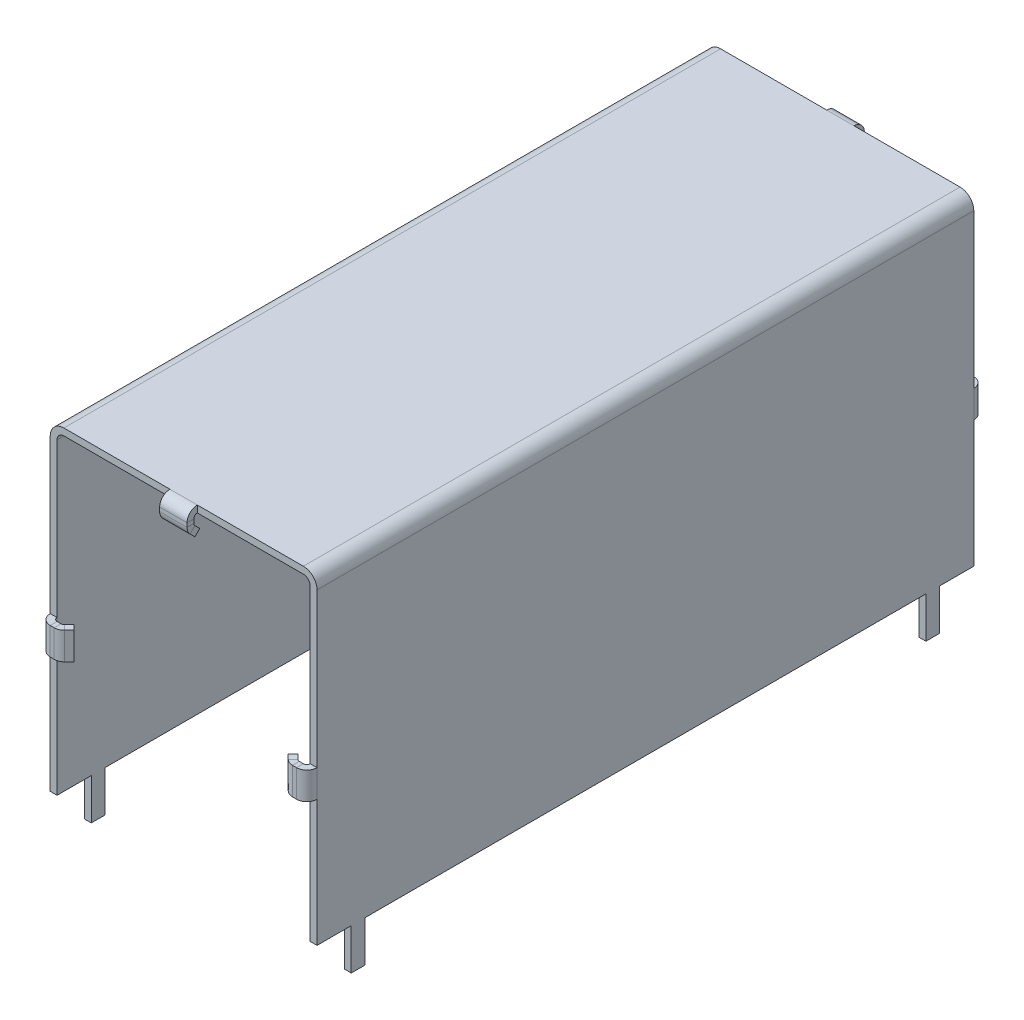
SolidWorks part; units mm, degrees
ref_plane "Спереди" through (0, 0, 0) normal (0, 0, 1) x (1, 0, 0)
ref_plane "Сверху" through (0, 0, 0) normal (0, 1, 0) x (1, 0, 0)
ref_plane "Справа" through (0, 0, 0) normal (1, 0, 0) x (0, 0, -1)
sketch "Эскиз1" plane through (0, 0, 0) normal (0, 0, 1) x (1, 0, 0)
  line L0 (0.5, 0) -> (0.5, 25.5)
  line L1 (0, 0) -> (0.5, 0)
  line L2 (0, 0) -> (0, 25.5)
  line L3 (1, 26.5) -> (18.5, 26.5)
  line L4 (19.5, 0) -> (19.5, 25.5)
  line L9 (1, 26) -> (18.5, 26)
  line L10 (19, 0) -> (19, 25.5)
  line L12 (0.5, 0.5) -> (19, 0.5) construction
  line L13 (0.5, 0.5) -> (0.5, 26) construction
  line L14 (19, 0.5) -> (19, 26) construction
  line L15 (19, 0) -> (19.5, 0)
  line L16 (0, 0) -> (19.5, 0) construction
  line L17 (0.5, 26) -> (19, 26) construction
  line L18 (19.5, 0) -> (19.5, 26.5) construction
  line L19 (0, 26.5) -> (19.5, 26.5) construction
  line L20 (0, 0) -> (0, 26.5) construction
  arc A4 (0.5, 25.5) -> (1, 26) centre (1, 25.5) cw
  arc A5 (19, 25.5) -> (18.5, 26) centre (18.5, 25.5) ccw
  arc A6 (19.5, 25.5) -> (18.5, 26.5) centre (18.5, 25.5) ccw
  arc A7 (0, 25.5) -> (1, 26.5) centre (1, 25.5) cw
  point P20 (19.5, 26.5)
  dimension "D4" = 0.5
  dimension "D5" = 1
  dimension "D1" = 26.5
  dimension "D2" = 19.5
  dimension "D3" = 0.5
extrude "Бобышка-Вытянуть1" add sketch "Эскиз1" along normal blind 48
sketch "Эскиз3" plane through (0, 0, 0) normal (-1, 0, 0) x (0, 0, 1)
  line L0 (48, 0) -> (0, 0) construction
  line L1 (46, 0) -> (44, 0)
  line L2 (46, 0) -> (46, -3.5035)
  line L3 (46, -3.5035) -> (44, -3.5035)
  line L4 (44, 0) -> (44, -3.5035)
  line L5 (48, 25.5) -> (48, 0) construction
  line L6 (4, 0) -> (2, 0)
  line L7 (4, 0) -> (4, -3.5035)
  line L8 (4, -3.5035) -> (2, -3.5035)
  line L9 (2, 0) -> (2, -3.5035)
  line L11 (0, 25.5) -> (0, 0) construction
  dimension "D1" = 2
  dimension "D2" = 2
  dimension "D4" = 2
  dimension "D3" = 2
extrude "Бобышка-Вытянуть2" add sketch "Эскиз3" against normal blind 0.5
sketch "Эскиз4" plane through (19.5, 0, 0) normal (1, 0, 0) x (0, 0, -1)
  line L1 (-46, -3.5035) -> (-44, -3.5035)
  line L2 (-46, -3.5035) -> (-46, 0)
  line L3 (-46, 0) -> (-44, 0)
  line L4 (-44, -3.5035) -> (-44, 0)
  line L5 (-4, -3.5035) -> (-2, -3.5035)
  line L6 (-4, -3.5035) -> (-4, 0)
  line L7 (-4, 0) -> (-2, 0)
  line L8 (-2, -3.5035) -> (-2, 0)
extrude "Бобышка-Вытянуть3" add sketch "Эскиз4" against normal blind 0.5
sketch "Эскиз7" plane through (0, 0, 0) normal (-1, 0, 0) x (0, 0, 1)
  line L0 (44, -3.5035) -> (46, -3.5035) construction
  line L1 (46, 0) -> (45.5, 0)
  line L2 (46, 0) -> (46, -3.5035)
  line L3 (46, -3.5035) -> (45.5, -3.5035)
  line L4 (45.5, 0) -> (45.5, -3.5035)
  line L5 (4, 0) -> (3.5, 0)
  line L6 (44, -3.5035) -> (44.5, -3.5035)
  line L7 (44, -3.5035) -> (44, 0)
  line L8 (44, 0) -> (44.5, 0)
  line L9 (44.5, -3.5035) -> (44.5, 0)
  line L10 (4, 0) -> (4, -3.5035)
  line L11 (4, -3.5035) -> (3.5, -3.5035)
  line L12 (3.5, 0) -> (3.5, -3.5035)
  line L13 (2, -3.5035) -> (2.5, -3.5035)
  line L14 (2, -3.5035) -> (2, 0)
  line L15 (2, 0) -> (2.5, 0)
  line L16 (2.5, -3.5035) -> (2.5, 0)
  dimension "D1" = 0.5
  dimension "D2" = 0.5
  dimension "D3" = 2
extrude "Вырез-Вытянуть2" cut sketch "Эскиз7" against normal blind 66.5
sketch "Эскиз8" plane through (0, 0, 48) normal (0, 0, 1) x (1, 0, 0)
  line L0 (18.5, 26.5) -> (1, 26.5) construction
  line L1 (8.75, 26.5) -> (10.75, 26.5)
  line L2 (8.75, 26.5) -> (8.75, 26)
  line L3 (8.75, 26) -> (10.75, 26)
  line L4 (10.75, 26.5) -> (10.75, 26)
  line L5 (1, 26) -> (18.5, 26) construction
  line L7 (19.5, 0) -> (19.5, 25.5) construction
  dimension "D1" = 2
  dimension "D2" = 8.75
sketch "Эскиз9" plane through (0, 0, 0) normal (-1, 0, 0) x (0, 0, 1)
  line L0 (48, 26.5) -> (48, 26) construction
  line L1 (48.5, 25.75) -> (48.5, 25.4571)
  line L2 (48.3536, 25.1036) -> (48, 24.75)
  line L3 (48, 25.5) -> (48, 0) construction
  line L4 (0, 26.5) -> (0, 25.5) construction
  line L5 (-0.5, 25.75) -> (-0.5, 25.4571)
  line L6 (-0.3536, 25.1036) -> (0, 24.75)
  line L7 (0, 25.5) -> (0, 0) construction
  line L8 (48, 26.25) -> (0, 26.25)
  arc A0 (48.3536, 25.1036) -> (48.5, 25.4571) centre (48, 25.4571) ccw
  arc A1 (48.5, 25.75) -> (48, 26.25) centre (48, 25.75) ccw
  arc A2 (-0.3536, 25.1036) -> (-0.5, 25.4571) centre (0, 25.4571) cw
  arc A3 (-0.5, 25.75) -> (0, 26.25) centre (0, 25.75) cw
  point P11 (48.5, 26.25)
  point P17 (48.5, 25.25)
  point P20 (48.5, 26.25)
  point P25 (-0.5, 26.25)
  dimension "D4" = 0.5
  dimension "D5" = 0.5
  dimension "D1" = 0.5
  dimension "D2" = 1
  dimension "D3" = 135
ref_plane "Плоскость4" through (0, 24.75, 48) normal (0, 0.7071, 0.7071) x (1, 0, 0)
sketch "Эскиз10" plane through (0, 24.75, 48) normal (0, 0.7071, 0.7071) x (1, 0, 0)
  line L1 (8.75, 0.25) -> (10.75, 0.25)
  line L2 (8.75, 0.25) -> (8.75, -0.25)
  line L3 (8.75, -0.25) -> (10.75, -0.25)
  line L4 (10.75, 0.25) -> (10.75, -0.25)
  dimension "D1" = 2
  dimension "D2" = 0.5
  dimension "D3" = 0.25
sweep "По траектории2" add profiles "Эскиз10" path "Эскиз9"
sketch "Эскиз11" plane through (0, 26.5, 0) normal (0, 1, 0) x (1, 0, 0)
  line L0 (19.5, 0) -> (18.5, 0) construction
  line L1 (19.25, -48) -> (19.25, 0)
  line L2 (18.75, 0.5) -> (18.4571, 0.5)
  line L3 (18.1036, 0.3536) -> (17.75, 0)
  line L4 (18.5, 0) -> (10.75, 0) construction
  line L7 (18.1036, -48.3536) -> (17.75, -48)
  line L8 (18.75, -48.5) -> (18.4571, -48.5)
  arc A0 (18.75, -48.5) -> (19.25, -48) centre (18.75, -48) ccw
  arc A1 (18.1036, -48.3536) -> (18.4571, -48.5) centre (18.4571, -48) ccw
  arc A2 (19.25, 0) -> (18.75, 0.5) centre (18.75, 0) ccw
  arc A3 (18.4571, 0.5) -> (18.1036, 0.3536) centre (18.4571, 0) ccw
  point P17 (19.25, 0.5)
  point P20 (18.25, 0.5)
  dimension "D2" = 0.5
  dimension "D1" = 0.5
  dimension "D3" = 1
  dimension "D4" = 135
ref_plane "Плоскость5" through (17.75, 26.5, 0) normal (-0.7071, 0, 0.7071) x (0.7071, 0, 0.7071)
sketch "Эскиз13" plane through (17.75, 26.5, 0) normal (-0.7071, 0, 0.7071) x (0.7071, 0, 0.7071)
  line L1 (-0.25, -12.25) -> (0.25, -12.25)
  line L2 (-0.25, -12.25) -> (-0.25, -14.25)
  line L3 (-0.25, -14.25) -> (0.25, -14.25)
  line L4 (0.25, -12.25) -> (0.25, -14.25)
  line L7 (0.8839, -26.5) -> (1.2374, -26.5) construction
  point P7 (1.0607, -26.5)
  dimension "D1" = 0.5
  dimension "D2" = 2
  dimension "D3" = 0.25
  dimension "D4" = 12.25
sketch "Эскиз14" plane through (0, 0, 0) normal (-1, 0, 0) x (0, 0, 1)
  line L0 (2.5, 0) -> (0, 0) construction
  line L1 (2.5, 0) -> (3.5, 0)
  line L2 (1.677, 0) -> (1.677, -4.0724)
  line L3 (1.677, -4.0724) -> (46.95, -4.0724)
  line L4 (46.95, 0) -> (46.95, -4.0724)
  line L5 (0, 25.5) -> (0, 0) construction
  line L6 (1.677, 0) -> (0, 0)
  line L7 (2.5, 0) -> (2.5, 3)
  line L8 (2.5, 3) -> (0, 3)
  line L9 (0, 0) -> (0, 3)
  line L10 (48, 25.5) -> (48, 0) construction
  line L12 (3.5, 0) -> (3.5, 3)
  line L13 (3.5, 3) -> (44.5, 3)
  line L14 (44.5, 0) -> (44.5, 3)
  line L15 (46.95, 0) -> (48, 0)
  line L16 (45.5, 0) -> (45.5, 3)
  line L17 (45.5, 3) -> (48, 3)
  line L18 (48, 0) -> (48, 3)
  line L19 (44.5, 0) -> (45.5, 0)
  dimension "D1" = 3
extrude "Вырез-Вытянуть3" cut sketch "Эскиз14" against normal blind 66.5
sweep "По траектории3" add profiles "Эскиз13" path "Эскиз11"
sketch "Эскиз15" plane through (0, 26.5, 0) normal (0, 1, 0) x (1, 0, 0)
  line L0 (0.25, -48) -> (0.25, 0)
  line L2 (0.75, 0.5) -> (1.0429, 0.5)
  line L3 (1.3964, 0.3536) -> (1.75, 0)
  line L4 (8.75, 0) -> (1, 0) construction
  line L5 (0, -48) -> (0, 0) construction
  line L8 (1.3964, -48.3536) -> (1.75, -48)
  line L9 (0.75, -48.5) -> (1.0429, -48.5)
  arc A0 (0.75, -48.5) -> (0.25, -48) centre (0.75, -48) cw
  arc A1 (1.3964, -48.3536) -> (1.0429, -48.5) centre (1.0429, -48) cw
  arc A2 (1.0429, 0.5) -> (1.3964, 0.3536) centre (1.0429, 0) cw
  arc A3 (0.25, 0) -> (0.75, 0.5) centre (0.75, 0) cw
  point P16 (1.25, 0.5)
  point P19 (0.25, 0.5)
  point P20 (0, 0)
  dimension "D2" = 0.5
  dimension "D1" = 0.25
  dimension "D3" = 1
  dimension "D4" = 135
ref_plane "Плоскость6" through (1.75, 26.5, 48) normal (0.7071, 0, -0.7071) x (-0.7071, 0, -0.7071)
sketch "Эскиз16" plane through (1.75, 26.5, 48) normal (0.7071, 0, -0.7071) x (-0.7071, 0, -0.7071)
  line L1 (0.25, -12.25) -> (-0.25, -12.25)
  line L2 (0.25, -12.25) -> (0.25, -14.25)
  line L3 (0.25, -14.25) -> (-0.25, -14.25)
  line L4 (-0.25, -12.25) -> (-0.25, -14.25)
  point P4 (0, 0)
  dimension "D1" = 0.5
  dimension "D2" = 0.25
sweep "По траектории4" add profiles "Эскиз16" path "Эскиз15"
